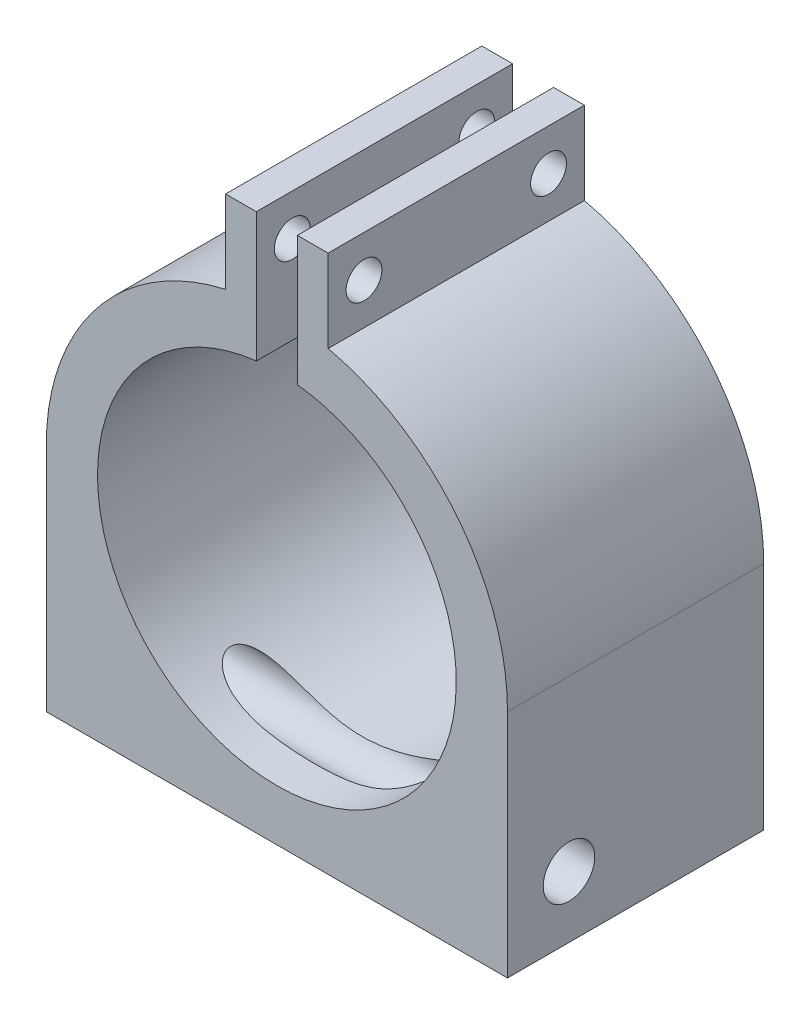
SolidWorks part; units mm, degrees
ref_plane "Front Plane" through (0, 0, 0) normal (0, 0, 1) x (1, 0, 0)
ref_plane "Top Plane" through (0, 0, 0) normal (0, 1, 0) x (1, 0, 0)
ref_plane "Right Plane" through (0, 0, 0) normal (1, 0, 0) x (0, 0, -1)
sketch "Sketch1" plane through (0, 0, 0) normal (0, 0, 1) x (1, 0, 0)
  line L0 (0, 0) -> (0, 22.5)
  line L2 (-5, 30) -> (5, 30)
  line L3 (-5, 30) -> (-5, 15)
  line L4 (-5, 15) -> (5, 15)
  line L5 (5, 30) -> (5, 15)
  line L6 (-5, 30) -> (5, 15) construction
  line L7 (-5, 15) -> (5, 30) construction
  line L8 (-22.5, 0) -> (22.5, 0)
  line L9 (-22.5, 0) -> (-22.5, -22.5)
  line L10 (-22.5, -22.5) -> (22.5, -22.5)
  line L11 (22.5, 0) -> (22.5, -22.5)
  circle A0 centre (0, 0) radius 22.5
  point P8 (24.8172, -24.9349)
  dimension "D1" = 45
  dimension "D2" = 10
  dimension "D3" = 15
  dimension "D4" = 45
  dimension "D5" = 22.5
extrude "Boss-Extrude2" add sketch "Sketch1" along normal blind 25 contours L3 L2 L5 L4 | A0 | L9 L8 L11 L10
sketch "Sketch3" plane through (0, 0, 25) normal (0, 0, 1) x (1, 0, 0)
  line L5 (-2, 35) -> (2, 35)
  line L6 (-2, 35) -> (-2, 0)
  line L7 (-2, 0) -> (2, 0)
  line L8 (2, 35) -> (2, 0)
  line L9 (-2, 35) -> (2, 0) construction
  line L10 (-2, 0) -> (2, 35) construction
  circle A0 centre (0, 0) radius 17.5
  point P3 (0.0446, 17.4999)
  point P4 (0, 17.5)
  dimension "D1" = 35
  dimension "D2" = 4
extrude "Cut-Extrude2" cut sketch "Sketch3" against normal blind 25 contours A0 | L7 L8 L5 L6
sketch "Sketch5" plane through (-22.5, 0, 0) normal (-1, 0, 0) x (0, 0, 1)
  line L0 (19, -16.5) -> (19, -22.5)
  line L1 (25, -22.5) -> (0, -22.5) construction
  line L2 (19, -22.5) -> (25, -22.5)
  circle A0 centre (19, -16.5) radius 2.5139
  dimension "D1" = 5.0277
  dimension "D2" = 6
  dimension "D3" = 6
extrude "Cut-Extrude3" cut sketch "Sketch5" against normal through all contours A0
sketch "Sketch7" plane through (-5, 0, 0) normal (-1, 0, 0) x (0, 0, 1)
  line L3 (3.5, 25.9687) -> (12.5, 25.9687)
  line L4 (12.5, 25.9687) -> (21.5, 25.9687)
  circle A0 centre (3.5, 25.9687) radius 1.75
  circle A1 centre (21.5, 25.9687) radius 1.75
  dimension "D1" = 3.5
  dimension "D2" = 3.5
  dimension "D3" = 9
  dimension "D4" = 9
extrude "Cut-Extrude4" cut sketch "Sketch7" against normal through all
